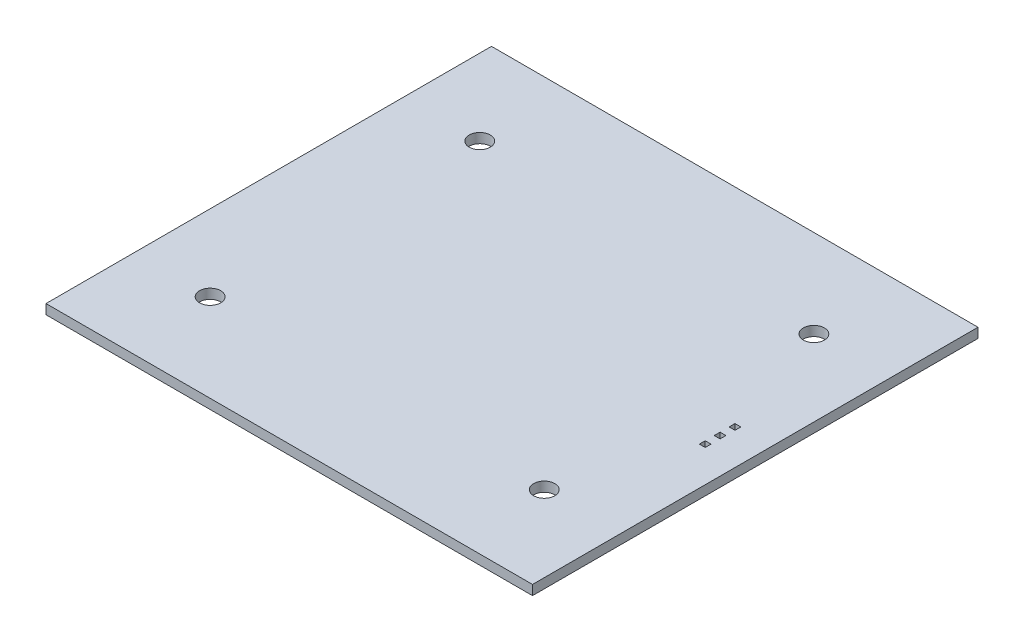
SolidWorks part; units mm, degrees
ref_plane "Front Plane" through (0, 0, 0) normal (0, 0, 1) x (1, 0, 0)
ref_plane "Top Plane" through (0, 0, 0) normal (0, 1, 0) x (1, 0, 0)
ref_plane "Right Plane" through (0, 0, 0) normal (1, 0, 0) x (0, 0, -1)
sketch "Sketch2" plane through (0, 0, 0) normal (0, 1, 0) x (1, 0, 0)
  line L1 (0, 0) -> (83, 0)
  line L2 (0, 0) -> (0, 76)
  line L3 (0, 76) -> (83, 76)
  line L4 (83, 0) -> (83, 76)
  dimension "D1" = 83
  dimension "D2" = 76
extrude "Boss-Extrude1" add sketch "Sketch2" along normal blind 1.66
sketch "Sketch3" plane through (0, 1.66, 0) normal (0, 1, 0) x (1, 0, 0)
  line L0 (0, 0) -> (83, 0) construction
  line L1 (76.5, 37.5) -> (77.5, 37.5)
  line L2 (76.5, 37.5) -> (76.5, 38.5)
  line L3 (76.5, 38.5) -> (77.5, 38.5)
  line L4 (77.5, 37.5) -> (77.5, 38.5)
  line L5 (76.5, 37.5) -> (77.5, 38.5) construction
  line L6 (76.5, 38.5) -> (77.5, 37.5) construction
  line L7 (0, 76) -> (0, 0) construction
  line L9 (76.5, 40.04) -> (77.5, 40.04)
  line L10 (76.5, 40.04) -> (76.5, 41.04)
  line L11 (76.5, 41.04) -> (77.5, 41.04)
  line L12 (77.5, 40.04) -> (77.5, 41.04)
  line L13 (76.5, 40.04) -> (77.5, 41.04) construction
  line L14 (76.5, 41.04) -> (77.5, 40.04) construction
  line L15 (76.5, 34.96) -> (77.5, 34.96)
  line L16 (76.5, 34.96) -> (76.5, 35.96)
  line L17 (76.5, 35.96) -> (77.5, 35.96)
  line L18 (77.5, 34.96) -> (77.5, 35.96)
  line L19 (76.5, 34.96) -> (77.5, 35.96) construction
  line L20 (76.5, 35.96) -> (77.5, 34.96) construction
  point P0 (77, 38)
  point P9 (77, 40.54)
  point P14 (77, 35.46)
  dimension "D1" = 1
  dimension "D2" = 1
  dimension "D3" = 38
  dimension "D4" = 77
  dimension "D5" = 2.54
  dimension "D6" = 2.54
extrude "Cut-Extrude1" cut sketch "Sketch3" against normal through all
sketch "Hole positions" plane through (0, 1.66, 0) normal (0, 1, 0) x (1, 0, 0)
  line L0 (0, 0) -> (83, 0) construction
  line L1 (13, 15) -> (70, 15)
  line L2 (13, 15) -> (13, 61)
  line L3 (13, 61) -> (70, 61)
  line L4 (70, 15) -> (70, 61)
  line L5 (0, 76) -> (0, 0) construction
  dimension "D1" = 15
  dimension "D2" = 13
  dimension "D3" = 61
  dimension "D4" = 70
hole_wizard "M3 Clearance Hole2" positions "Sketch8" profile "Sketch7" hole size "M3" standard "ANSI Metric" end condition through all
sketch "Sketch8" plane through (0, 1.66, 0) normal (0, 1, 0) x (1, 0, 0)
  point P0 (13, 61)
  point P3 (70, 61)
  point P6 (70, 15)
  point P9 (13, 15)
sketch "Sketch7" plane through (13, 1.66, -61) normal (1, 0, 0) x (0, 0, 1)
  line L0 (0, 0) -> (0, 1.66)
  line L1 (0, 1.66) -> (1.8, 1.66)
  line L2 (1.8, 1.66) -> (1.8, 0)
  line L5 (1.8, 0) -> (0, 0)
  line L11 (0, -6.35) -> (0, 107.95) construction
  dimension "Thru Hole Dia." = 3.6
  dimension "Thru Hole Depth" = 1.66
